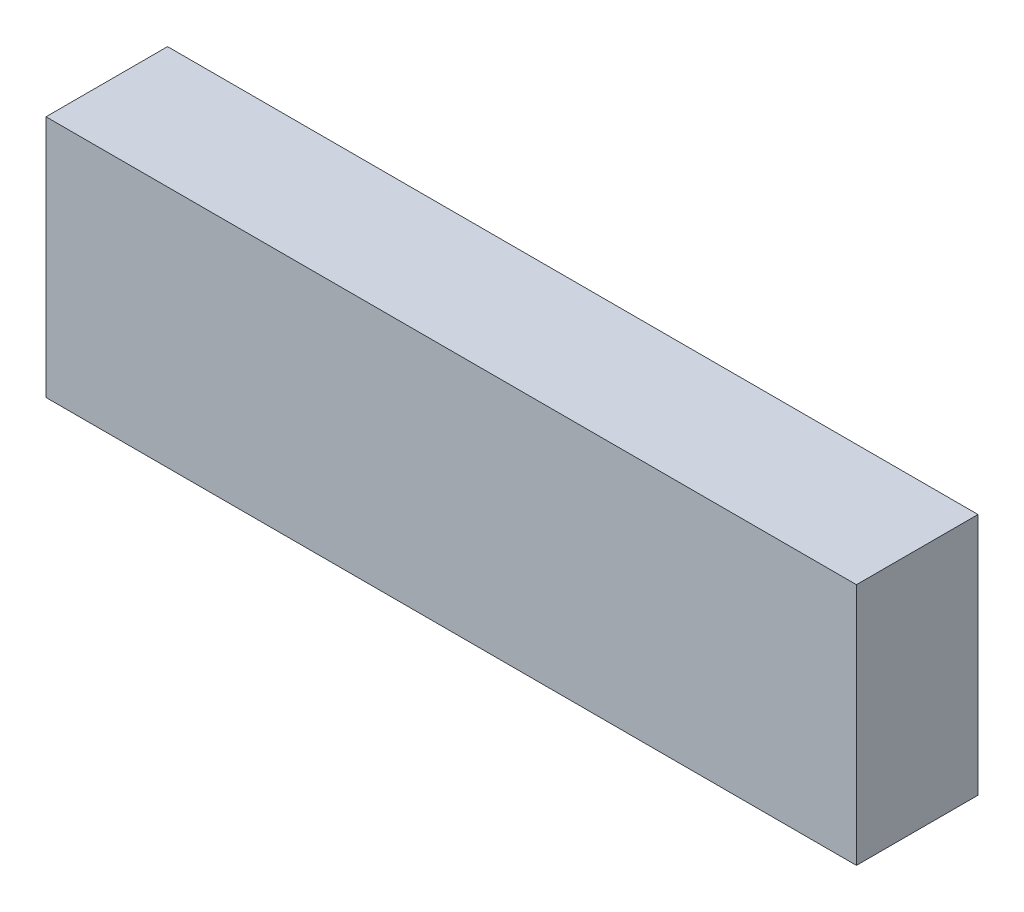
SolidWorks part; units mm, degrees
ref_plane "Front Plane" through (0, 0, 0) normal (0, 0, 1) x (1, 0, 0)
ref_plane "Top Plane" through (0, 0, 0) normal (0, 1, 0) x (1, 0, 0)
ref_plane "Right Plane" through (0, 0, 0) normal (1, 0, 0) x (0, 0, -1)
sketch "Sketch1" plane through (0, 0, 0) normal (1, 0, 0) x (0, 0, -1)
  line L1 (0, 0) -> (6, 0)
  line L2 (0, 0) -> (0, 12)
  line L3 (0, 12) -> (6, 12)
  line L4 (6, 0) -> (6, 12)
  dimension "D1" = 12
  dimension "D2" = 6
extrude "Boss-Extrude1" add sketch "Sketch1" along normal blind 40
